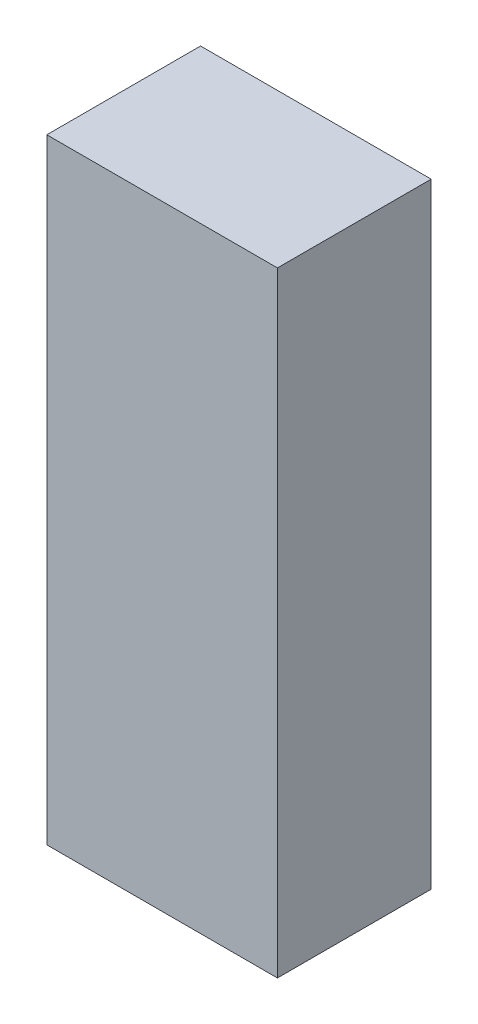
SolidWorks part; units mm, degrees
ref_plane "Front Plane" through (0, 0, 0) normal (0, 0, 1) x (1, 0, 0)
ref_plane "Top Plane" through (0, 0, 0) normal (0, 1, 0) x (1, 0, 0)
ref_plane "Right Plane" through (0, 0, 0) normal (1, 0, 0) x (0, 0, -1)
sketch "Sketch1" plane through (0, 0, 0) normal (0, 0, 1) x (1, 0, 0)
  line L1 (0, 0) -> (15, 0)
  line L2 (0, 0) -> (0, 40)
  line L3 (0, 40) -> (15, 40)
  line L4 (15, 0) -> (15, 40)
  dimension "D1" = 40
  dimension "D2" = 15
extrude "Boss-Extrude1" add sketch "Sketch1" along normal blind 10
